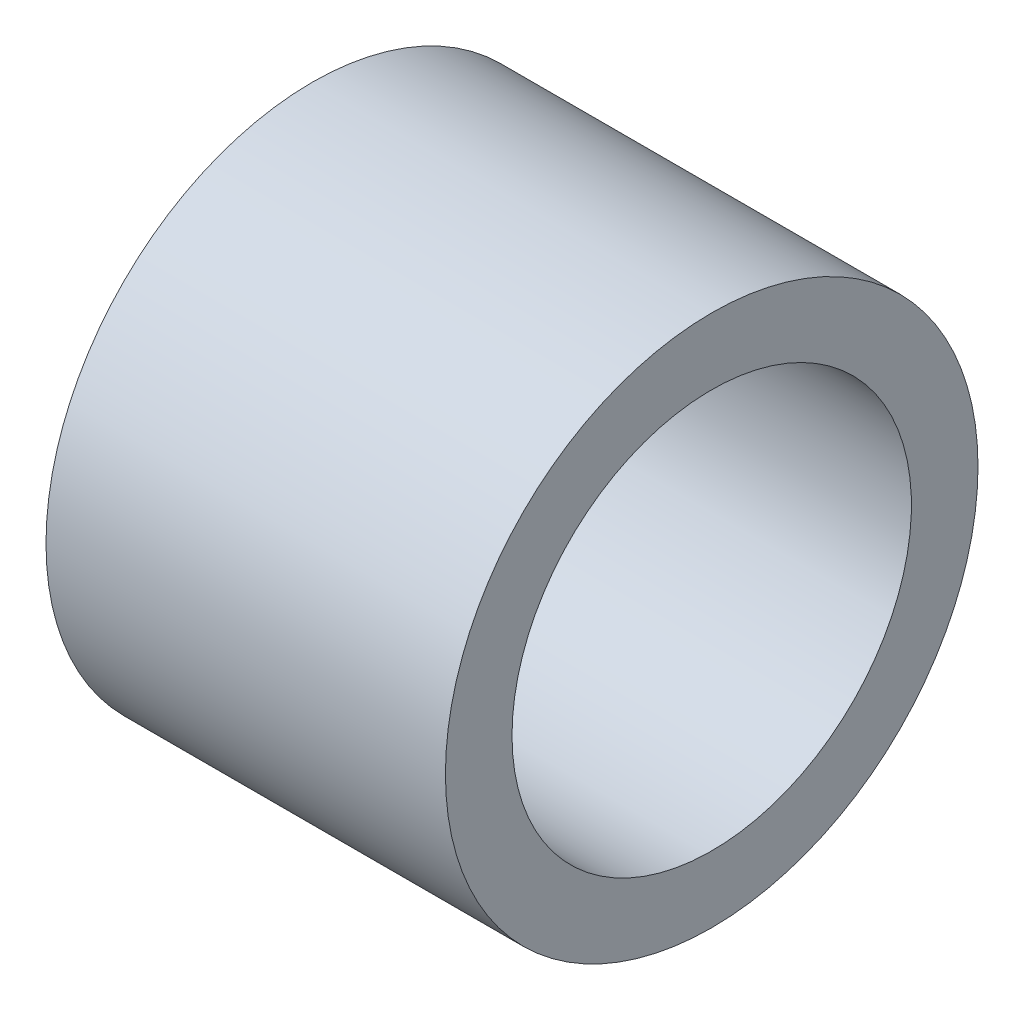
SolidWorks part; units mm, degrees
material "MCナイロン"
ref_plane "Front Plane" through (0, 0, 0) normal (0, 0, 1) x (1, 0, 0)
ref_plane "Top Plane" through (0, 0, 0) normal (0, 1, 0) x (1, 0, 0)
ref_plane "Right Plane" through (0, 0, 0) normal (1, 0, 0) x (0, 0, -1)
sketch "Sketch1" plane through (0, 0, 0) normal (0, 0, 1) x (1, 0, 0)
  line L0 (0, 0) -> (6, 0) construction
  line L1 (0, 3) -> (6, 3)
  line L2 (0, -3) -> (6, -3) construction
  line L3 (0, 3) -> (0, 4)
  line L4 (0, 4) -> (6, 4)
  line L5 (6, 3) -> (6, 4)
  dimension "D" = 8
  dimension "V" = 6
  dimension "T" = 6
revolve "Revolve1" add sketch "Sketch1" angle 360 about L0
